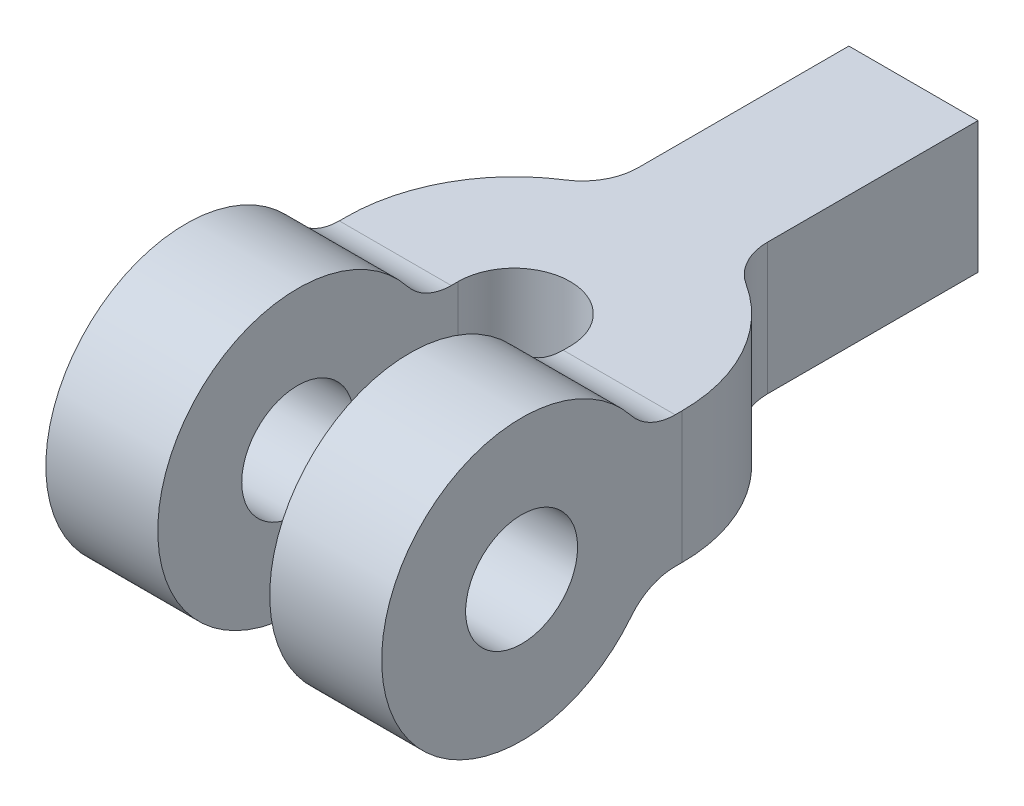
SolidWorks part; units mm, degrees
ref_plane "Front Plane" through (0, 0, 0) normal (0, 0, 1) x (1, 0, 0)
ref_plane "Top Plane" through (0, 0, 0) normal (0, 1, 0) x (1, 0, 0)
ref_plane "Right Plane" through (0, 0, 0) normal (1, 0, 0) x (0, 0, -1)
sketch "Sketch2" plane through (0, 0, 0) normal (0, 1, 0) x (1, 0, 0)
  line L1 (60, -125) -> (-60, -125)
  line L2 (60, -125) -> (60, 125)
  line L3 (60, 125) -> (-60, 125)
  line L4 (-60, -125) -> (-60, 125)
  line L5 (60, -125) -> (-60, 125) construction
  line L6 (60, 125) -> (-60, -125) construction
  point P0 (0, 0)
  dimension "D1" = 120
  dimension "D2" = 250
extrude "Boss-Extrude1" add sketch "Sketch2" along normal blind 100
sketch "Sketch3" plane through (0, 100, 0) normal (0, 1, 0) x (1, 0, 0)
  line L0 (0, 0) -> (0, 125) construction
  line L1 (60, 125) -> (-60, 125) construction
  line L2 (0, 0) -> (0, -125) construction
  line L3 (-60, -125) -> (60, -125) construction
  line L4 (-23.0717, 125) -> (-23.0717, 49.7707)
  line L5 (23.0717, 125) -> (23.0717, 49.7707)
  line L6 (-20, -17.6446) -> (-20, -125)
  line L7 (20, -17.6446) -> (20, -125)
  line L10 (-60, 125) -> (-60, -125)
  line L11 (-60, -125) -> (60, -125)
  line L12 (60, -125) -> (60, 125)
  line L13 (60, 125) -> (-60, 125)
  line L14 (-60, 125) -> (-60, -125)
  line L15 (-60, -125) -> (60, -125)
  line L16 (60, -125) -> (60, 125)
  line L17 (60, 125) -> (-60, 125)
  arc A0 (-32.3038, 32.9169) -> (32.3038, 32.9169) centre (0, -17.6446) ccw
  circle A1 centre (0, -17.6446) radius 20
  arc A2 (-32.3038, 32.9169) -> (-23.0717, 49.7707) centre (-43.0717, 49.7707) ccw
  arc A3 (32.3038, 32.9169) -> (23.0717, 49.7707) centre (43.0717, 49.7707) cw
  dimension "D1" = 40
  dimension "D2" = 120
  dimension "D4" = 20
  dimension "D5" = 20
  dimension "D3" = 0
sketch "Sketch4" plane through (0, 100, 0) normal (0, 1, 0) x (1, 0, 0)
  line L0 (-23.0717, 125) -> (-23.0717, 49.7707) construction
  line L1 (23.0717, 125) -> (23.0717, 49.7707) construction
  line L2 (20, -17.6446) -> (20, -125) construction
  line L3 (-20, -17.6446) -> (-20, -125) construction
  line L4 (-60, -125) -> (60, -125)
  line L5 (60, -125) -> (60, 125)
  line L6 (60, 125) -> (-60, 125)
  line L7 (-60, 125) -> (-60, -125)
  line L8 (-60, -125) -> (60, -125)
  line L9 (60, -125) -> (60, 125)
  line L10 (60, 125) -> (-60, 125)
  line L11 (-60, 125) -> (-60, -125)
  line L12 (-23.0717, 125) -> (-23.0717, 49.7707)
  line L13 (23.0717, 125) -> (23.0717, 49.7707)
  line L14 (20, -17.6446) -> (20, -125)
  line L15 (-20, -17.6446) -> (-20, -125)
  arc A0 (-32.3038, 32.9169) -> (-23.0717, 49.7707) centre (-43.0717, 49.7707) ccw construction
  circle A1 centre (0, -17.6446) radius 20
  circle A2 centre (0, -17.6446) radius 20
  arc A3 (-32.3038, 32.9169) -> (32.3038, 32.9169) centre (0, -17.6446) ccw construction
  arc A4 (23.0717, 49.7707) -> (32.3038, 32.9169) centre (43.0717, 49.7707) ccw construction
  arc A5 (-32.3038, 32.9169) -> (-23.0717, 49.7707) centre (-43.0717, 49.7707) ccw
  arc A6 (-32.3038, 32.9169) -> (32.3038, 32.9169) centre (0, -17.6446) ccw
  arc A7 (23.0717, 49.7707) -> (32.3038, 32.9169) centre (43.0717, 49.7707) ccw
  line M6 (-60, 125) -> (-60, -125)
  line M9 (60, 125) -> (-60, 125)
  dimension "D1" = 0
  dimension "D2" = 0
extrude "Cut-Extrude1" cut sketch "Sketch4" against normal blind 100 contours A6 A5 L12 L10 M6 | L13 A7 A6 L9 M9 | A2 | L15 A6 L14 A2 | A6 L15 L8 L14
sketch "Sketch5" plane through (60, 0, 0) normal (1, 0, 0) x (0, 0, -1)
  line L0 (-125, 100) -> (-125, 0) construction
  line L1 (-125, 0) -> (-17.6446, 0) construction
  line L2 (125, 73.475) -> (125, 26.525)
  line L3 (-20.1372, 73.475) -> (125, 73.475)
  line L4 (125, 0) -> (125, 100) construction
  line L5 (-75, 50) -> (125, 50) construction
  line L6 (-20.1372, 26.525) -> (125, 26.525)
  line L7 (125, 100) -> (49.7707, 100) construction
  line L8 (49.7707, 0) -> (125, 0) construction
  line L9 (49.7707, 100) -> (32.9169, 100) construction
  line L10 (32.9169, 0) -> (49.7707, 0) construction
  line L11 (32.9169, 100) -> (-17.6446, 100) construction
  line L12 (-17.6446, 0) -> (32.9169, 0) construction
  line L13 (-17.6446, 100) -> (-125, 100) construction
  line L14 (125, 100) -> (49.7707, 100)
  line L15 (49.7707, 0) -> (125, 0)
  line L16 (125, 0) -> (125, 100)
  line L17 (49.7707, 100) -> (32.9169, 100)
  line L18 (32.9169, 0) -> (49.7707, 0)
  line L19 (32.9169, 100) -> (-17.6446, 100)
  line L20 (-17.6446, 0) -> (32.9169, 0)
  line L21 (-125, 0) -> (-17.6446, 0)
  line L22 (-17.6446, 100) -> (-125, 100)
  line L23 (-125, 100) -> (-125, 0)
  arc A0 (-35.8123, 81.0536) -> (-35.8123, 18.9464) centre (-75, 50) ccw
  circle A1 centre (-75, 50) radius 20
  arc A2 (-20.1372, 73.475) -> (-35.8123, 81.0536) centre (-20.1372, 93.475) cw
  arc A3 (-20.1372, 26.525) -> (-35.8123, 18.9464) centre (-20.1372, 6.525) ccw
  dimension "D2" = 100
  dimension "D3" = 20
  dimension "D4" = 20
  dimension "D1" = 50
extrude "Cut-Extrude5" cut sketch "Sketch5" against normal through all
scale "Scale1" scale about centroid uniform scaling yes scale factor 0.35
